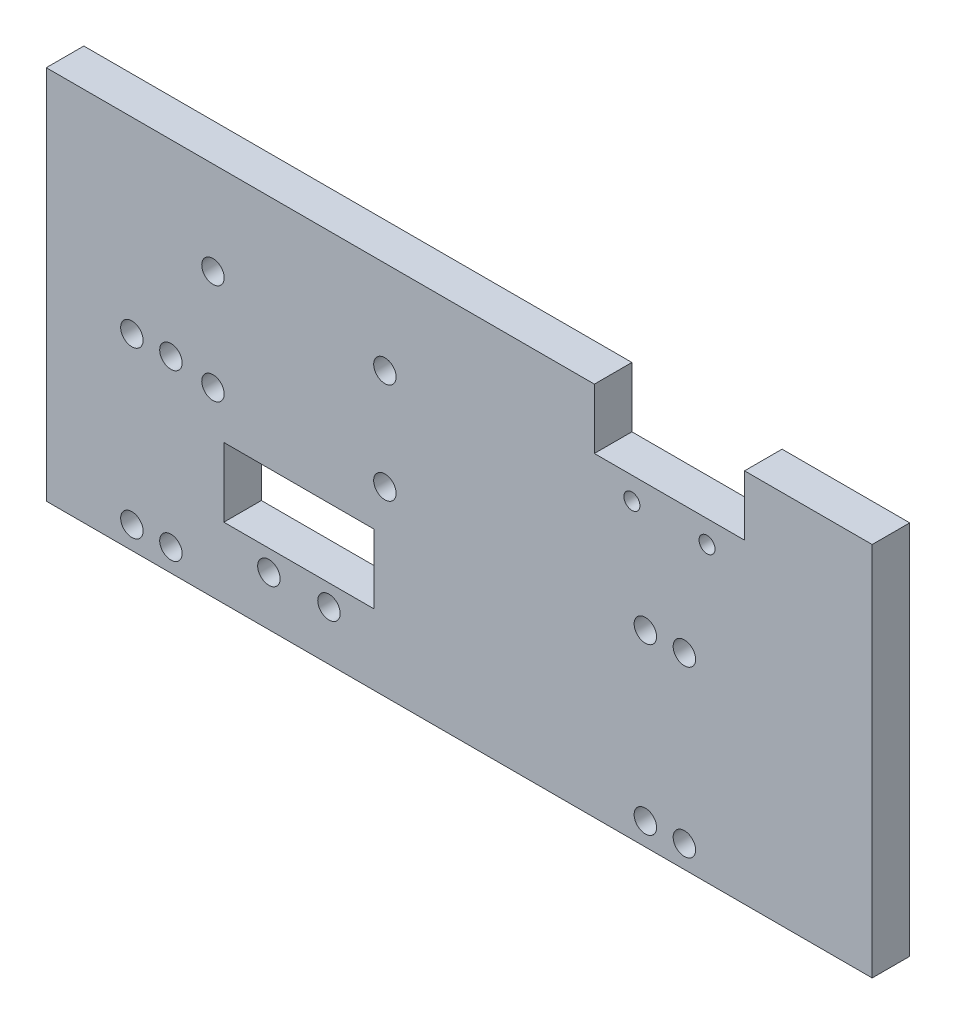
SolidWorks part; units mm, degrees
ref_plane "Front Plane" through (0, 0, 0) normal (0, 0, 1) x (1, 0, 0)
ref_plane "Top Plane" through (0, 0, 0) normal (0, 1, 0) x (1, 0, 0)
ref_plane "Right Plane" through (0, 0, 0) normal (1, 0, 0) x (0, 0, -1)
sketch "Sketch1" plane through (0, 0, 0) normal (0, 0, 1) x (1, 0, 0)
  line L1 (127, -31.75) -> (-127, -31.75)
  line L2 (127, -31.75) -> (127, 31.75)
  line L3 (127, 31.75) -> (-127, 31.75)
  line L4 (-127, -31.75) -> (-127, 31.75)
  line L5 (127, -31.75) -> (-127, 31.75) construction
  line L6 (127, 31.75) -> (-127, -31.75) construction
  point P0 (0, 0)
  dimension "D1" = 254
  dimension "D2" = 63.5
extrude "Boss-Extrude1" add sketch "Sketch1" along normal blind 6.35
hole_wizard "#6 Clearance Hole1" positions "Sketch2" profile "Sketch3" hole size "#6" standard "ANSI Inch"
sketch "Sketch2" plane through (0, 0, 6.35) normal (0, 0, 1) x (1, 0, 0)
  line L1 (-112.522, -27.94) -> (-105.918, -27.94)
  line L2 (-112.522, -27.94) -> (-112.522, 0)
  line L3 (-112.522, 0) -> (-105.918, 0)
  line L4 (-105.918, -27.94) -> (-105.918, 0)
  line L5 (-112.522, -27.94) -> (-105.918, 0) construction
  line L6 (-112.522, 0) -> (-105.918, -27.94) construction
  line L7 (-127, 31.75) -> (-127, -31.75) construction
  line L9 (-127, -31.75) -> (127, -31.75) construction
  point P2 (-105.918, 0)
  point P481 (-112.522, -27.94)
  point P482 (-112.522, 0)
  point P483 (-105.918, -27.94)
  point P496 (-109.22, -13.97)
  dimension "D1" = 27.94
  dimension "D2" = 6.604
  dimension "D3" = 17.78
  dimension "D4" = 3.81
sketch "Sketch3" plane through (-105.918, 0, 6.35) normal (1, 0, 0) x (0, -1, 0)
  line L0 (0, 0) -> (0, 7.4908)
  line L1 (0, 7.4908) -> (1.8986, 6.35)
  line L2 (1.8986, 6.35) -> (1.8986, 0)
  line L5 (1.8986, 0) -> (0, 0)
  line L10 (0, 7.4908) -> (-1.8987, 6.35) construction
  line L11 (0, -6.35) -> (0, 107.95) construction
  dimension "Hole Dia." = 3.7973
  dimension "Hole Depth" = 6.35
  dimension "Drill Angle" = 118
ref_plane "Plane1" through (-60.96, 0, 0) normal (-1, 0, 0) x (0, 0, 1)
hole_wizard "#6 Clearance Hole2" positions "Sketch19" profile "Sketch20" hole size "#6" standard "ANSI Inch"
sketch "Sketch19" plane through (0, 0, 0) normal (0, 0, -1) x (-1, 0, 0)
  line L0 (69.723, -1.016) -> (98.806, -1.016)
  line L2 (127, -31.75) -> (-127, -31.75) construction
  line L3 (127, 31.75) -> (127, -31.75) construction
  point P0 (98.806, -1.016)
  point P2 (69.723, -1.016)
  dimension "D1" = 29.083
  dimension "D2" = 30.734
  dimension "D3" = 28.194
sketch "Sketch20" plane through (-98.806, -1.016, 0) normal (1, 0, 0) x (0, 1, 0)
  line L0 (0, 0) -> (0, 8.7608)
  line L1 (0, 8.7608) -> (1.8986, 7.62)
  line L2 (1.8986, 7.62) -> (1.8986, 0)
  line L5 (1.8986, 0) -> (0, 0)
  line L10 (0, 8.7608) -> (-1.8987, 7.62) construction
  line L11 (0, -6.35) -> (0, 107.95) construction
  dimension "Hole Dia." = 3.7973
  dimension "Hole Depth" = 7.62
  dimension "Drill Angle" = 118
sketch "Sketch21" plane through (0, 0, 0) normal (0, 0, -1) x (-1, 0, 0)
  line L0 (69.723, -1.016) -> (98.806, -1.016)
  line L1 (96.9645, -19.812) -> (71.5645, -19.812)
  line L2 (96.9645, -19.812) -> (96.9645, -8.128)
  line L3 (96.9645, -8.128) -> (71.5645, -8.128)
  line L4 (71.5645, -19.812) -> (71.5645, -8.128)
  line L5 (96.9645, -19.812) -> (71.5645, -8.128) construction
  line L6 (96.9645, -8.128) -> (71.5645, -19.812) construction
  line L7 (84.2645, -1.016) -> (84.2645, -26.924)
  point P0 (84.2645, -13.97)
  dimension "D1" = 7.112
  dimension "D2" = 18.796
  dimension "D3" = 25.4
extrude "Cut-Extrude7" cut sketch "Sketch21" against normal through all contours L7 L3 L4 L1 | L3 L7 L1 L2
hole_wizard "#6 Clearance Hole3" positions "Sketch22" profile "Sketch23" hole size "#6" standard "ANSI Inch"
sketch "Sketch22" plane through (0, 0, 0) normal (0, 0, -1) x (-1, 0, 0)
  line L0 (69.723, 16.002) -> (98.806, 16.002)
  line L2 (127, 31.75) -> (127, -31.75) construction
  circle A0 centre (69.723, -1.016) radius 1.8987 construction
  point P0 (69.723, 16.002)
  point P2 (98.806, 16.002)
  dimension "D1" = 17.018
  dimension "D2" = 29.083
  dimension "D3" = 28.194
sketch "Sketch23" plane through (-69.723, 16.002, 0) normal (1, 0, 0) x (0, 1, 0)
  line L0 (0, 0) -> (0, 8.7608)
  line L1 (0, 8.7608) -> (1.8986, 7.62)
  line L2 (1.8986, 7.62) -> (1.8986, 0)
  line L5 (1.8986, 0) -> (0, 0)
  line L10 (0, 8.7608) -> (-1.8987, 7.62) construction
  line L11 (0, -6.35) -> (0, 107.95) construction
  dimension "Hole Dia." = 3.7973
  dimension "Hole Depth" = 7.62
  dimension "Drill Angle" = 118
hole_wizard "#6 Clearance Hole4" positions "Sketch24" profile "Sketch25" hole size "#6" standard "ANSI Inch"
sketch "Sketch24" plane through (0, 0, 0) normal (0, 0, -1) x (-1, 0, 0)
  line L2 (79.1845, -23.3528) -> (89.3445, -23.3528)
  line L5 (69.723, -1.016) -> (98.806, -1.016)
  line L9 (127, -31.75) -> (-127, -31.75) construction
  line L11 (84.2645, -23.3528) -> (84.2645, 4.4861)
  point P0 (79.1845, -23.3528)
  point P2 (89.3445, -23.3528)
  point P36 (84.2645, -1.016)
  dimension "D1" = 10.16
  dimension "D2" = 0
  dimension "D3" = 8.3972
sketch "Sketch25" plane through (-79.1845, -23.3528, 0) normal (1, 0, 0) x (0, 1, 0)
  line L0 (0, 0) -> (0, 8.7608)
  line L1 (0, 8.7608) -> (1.8986, 7.62)
  line L2 (1.8986, 7.62) -> (1.8986, 0)
  line L5 (1.8986, 0) -> (0, 0)
  line L10 (0, 8.7608) -> (-1.8986, 7.62) construction
  line L11 (0, -6.35) -> (0, 107.95) construction
  dimension "Hole Dia." = 3.7973
  dimension "Hole Depth" = 7.62
  dimension "Drill Angle" = 118
sketch "Sketch27" plane through (0, 0, 6.35) normal (0, 0, 1) x (1, 0, 0)
  line L0 (-127, -31.75) -> (127, -31.75) construction
  line L1 (127, 31.75) -> (12.7, 31.75)
  line L2 (127, 31.75) -> (127, -31.75)
  line L3 (127, -31.75) -> (12.7, -31.75)
  line L4 (12.7, 31.75) -> (12.7, -31.75)
  dimension "D1" = 114.3
extrude "Cut-Extrude9" cut sketch "Sketch27" against normal through all
sketch "Sketch28" plane through (0, 0, 6.35) normal (0, 0, 1) x (1, 0, 0)
  line L0 (-127, 31.75) -> (-127, -31.75) construction
  line L1 (-34.29, 31.75) -> (-8.89, 31.75)
  line L2 (-34.29, 31.75) -> (-34.29, 21.59)
  line L3 (-34.29, 21.59) -> (-8.89, 21.59)
  line L4 (-8.89, 31.75) -> (-8.89, 21.59)
  line L5 (12.7, 31.75) -> (-127, 31.75) construction
  dimension "D1" = 92.71
  dimension "D2" = 0
  dimension "D3" = 10.16
  dimension "D4" = 25.4
extrude "Cut-Extrude10" cut sketch "Sketch28" against normal blind 33.02
hole_wizard "Tap Drill for #6-32 Tap1" positions "Sketch29" profile "Sketch30" hole size "#6-32" standard "ANSI Inch"
sketch "Sketch29" plane through (0, 0, 6.35) normal (0, 0, 1) x (1, 0, 0)
  line L0 (-27.94, 17.78) -> (-15.24, 17.78)
  line L2 (-34.29, 21.59) -> (-8.89, 21.59) construction
  point P0 (-27.94, 17.78)
  point P2 (-15.24, 17.78)
  point P9 (-21.59, 17.78)
  point P12 (-21.59, 21.59)
  dimension "D1" = 12.7
  dimension "D2" = 0
  dimension "D3" = 3.81
sketch "Sketch30" plane through (-27.94, 17.78, 6.35) normal (1, 0, 0) x (0, -1, 0)
  line L0 (0, 0) -> (0, 10.9727)
  line L1 (0, 10.9727) -> (1.3525, 10.16)
  line L2 (1.3525, 10.16) -> (1.3525, 0)
  line L5 (1.3525, 0) -> (0, 0)
  line L10 (0, 10.9727) -> (-1.3525, 10.16) construction
  line L11 (0, -6.35) -> (0, 107.95) construction
  dimension "Hole Dia." = 2.7051
  dimension "Hole Depth" = 10.16
  dimension "Drill Angle" = 118
hole_wizard "#6 Clearance Hole5" positions "Sketch31" profile "Sketch32" hole size "#6" standard "ANSI Inch"
sketch "Sketch31" plane through (0, 0, 6.35) normal (0, 0, 1) x (1, 0, 0)
  line L1 (-25.6688, 0) -> (-19.0648, 0)
  line L2 (-25.6688, 0) -> (-25.6688, -27.94)
  line L3 (-25.6688, -27.94) -> (-19.0648, -27.94)
  line L4 (-19.0648, 0) -> (-19.0648, -27.94)
  line L5 (-127, -31.75) -> (12.7, -31.75) construction
  point P0 (-25.6688, 0)
  point P2 (-19.0648, 0)
  point P4 (-25.6688, -27.94)
  point P6 (-19.0648, -27.94)
  dimension "D1" = 6.604
  dimension "D2" = 27.94
  dimension "D3" = 3.81
sketch "Sketch32" plane through (-25.6688, 0, 6.35) normal (1, 0, 0) x (0, -1, 0)
  line L0 (0, 0) -> (0, 11.3008)
  line L1 (0, 11.3008) -> (1.8986, 10.16)
  line L2 (1.8986, 10.16) -> (1.8986, 0)
  line L5 (1.8986, 0) -> (0, 0)
  line L10 (0, 11.3008) -> (-1.8987, 10.16) construction
  line L11 (0, -6.35) -> (0, 107.95) construction
  dimension "Hole Dia." = 3.7973
  dimension "Hole Depth" = 10.16
  dimension "Drill Angle" = 118
